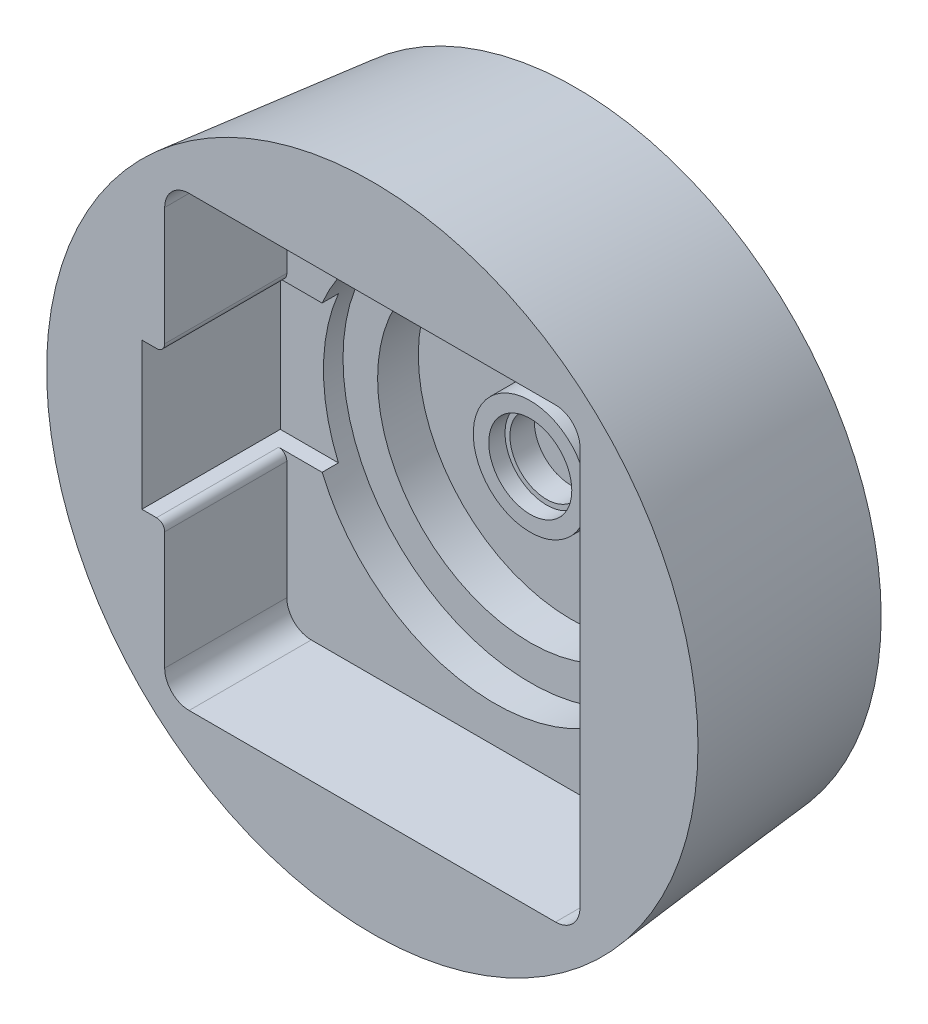
SolidWorks part; units mm, degrees
ref_plane "Front" through (0, 0, 0) normal (0, 0, 1) x (1, 0, 0)
ref_plane "Top" through (0, 0, 0) normal (0, 1, 0) x (1, 0, 0)
ref_plane "Right" through (0, 0, 0) normal (1, 0, 0) x (0, 0, -1)
sketch "Sketch2" plane through (0, 0, 0) normal (0, 1, 0) x (1, 0, 0)
  line L0 (0, 25) -> (37.5, 25)
  line L1 (37.5, 25) -> (40, 0)
  line L2 (40, 0) -> (0, 0)
  line L3 (0, 0) -> (0, 25)
  dimension "D1" = 40
  dimension "D2" = 37.5
  dimension "D3" = 25
revolve "Revolve1" add sketch "Sketch2" angle 360 about L3
sketch "Sketch4" plane through (0, 0, 0) normal (0, 0, 1) x (1, 0, 0)
  line L1 (-25.5, -27.5) -> (25.5, -27.5)
  line L2 (-25.5, -27.5) -> (-25.5, 27.5)
  line L3 (-25.5, 27.5) -> (25.5, 27.5)
  line L4 (25.5, -27.5) -> (25.5, 27.5)
  line L5 (-25.5, -27.5) -> (25.5, 27.5) construction
  line L6 (-25.5, 27.5) -> (25.5, -27.5) construction
  point P0 (0, 0)
  dimension "D1" = 55
  dimension "D2" = 51
extrude "Cut-Extrude1" cut sketch "Sketch4" against normal blind 15
fillet "Fillet1" radius 3 4 edges at (25.5, -27.5, -7.5) (-25.5, -27.5, -7.5) (-25.5, 27.5, -7.5) (25.5, 27.5, -7.5)
sketch "Sketch7" plane through (0, 0, 0) normal (0, 0, 1) x (1, 0, 0)
  line L0 (40, 0) -> (-40, 0) construction
  line L1 (-25.5, 24.5) -> (-25.5, -24.5) construction
  line L3 (-28.3, -9) -> (-18.3, -9)
  line L4 (-28.3, -9) -> (-28.3, 9)
  line L5 (-28.3, 9) -> (-18.3, 9)
  line L6 (-18.3, -9) -> (-18.3, 9)
  line L7 (-28.3, -9) -> (-18.3, 9) construction
  line L8 (-28.3, 9) -> (-18.3, -9) construction
  circle A1 centre (0, 0) radius 40 construction
  point P0 (-23.3, 0)
  point P3 (-25.5, 0)
  point P11 (0, 0)
  dimension "D1" = 2.8
  dimension "D2" = 18
  dimension "D3" = 10
extrude "Cut-Extrude5" cut sketch "Sketch7" against normal offset from surface (17 mm away) 2 up to face at (0, 0, -15) offset beyond the face yes
sketch "Sketch8" plane through (0, 0, -15) normal (0, 0, 1) x (1, 0, 0)
  circle A0 centre (0, 0) radius 23
  dimension "D1" = 46
extrude "Cut-Extrude6" cut sketch "Sketch8" against normal blind 4.4
sketch "Sketch10" plane through (0, 0, -19.4) normal (0, 0, 1) x (1, 0, 0)
  circle A0 centre (0, 0) radius 18.75
  dimension "D1" = 37.5
extrude "Cut-Extrude7" cut sketch "Sketch10" against normal blind 5
sketch "Sketch11" plane through (0, 0, -24.4) normal (0, 0, 1) x (1, 0, 0)
  circle A0 centre (0, 0) radius 7
  dimension "D1" = 14
extrude "Boss-Extrude3" add sketch "Sketch11" along normal blind 5
sketch "Sketch12" plane through (0, 0, -19.4) normal (0, 0, 1) x (1, 0, 0)
  circle A0 centre (0, 0) radius 5.1
  dimension "D1" = 10.2
extrude "Cut-Extrude8" cut sketch "Sketch12" against normal blind 2
sketch "Sketch13" plane through (0, 0, -21.4) normal (0, 0, 1) x (1, 0, 0)
  circle A0 centre (0, 0) radius 4.5
  dimension "D1" = 9
extrude "Cut-Extrude9" cut sketch "Sketch13" against normal blind 3
fillet "Fillet2" radius 1 2 edges at (-25.5, -9, -7.5) (-25.5, 9, -7.5)
